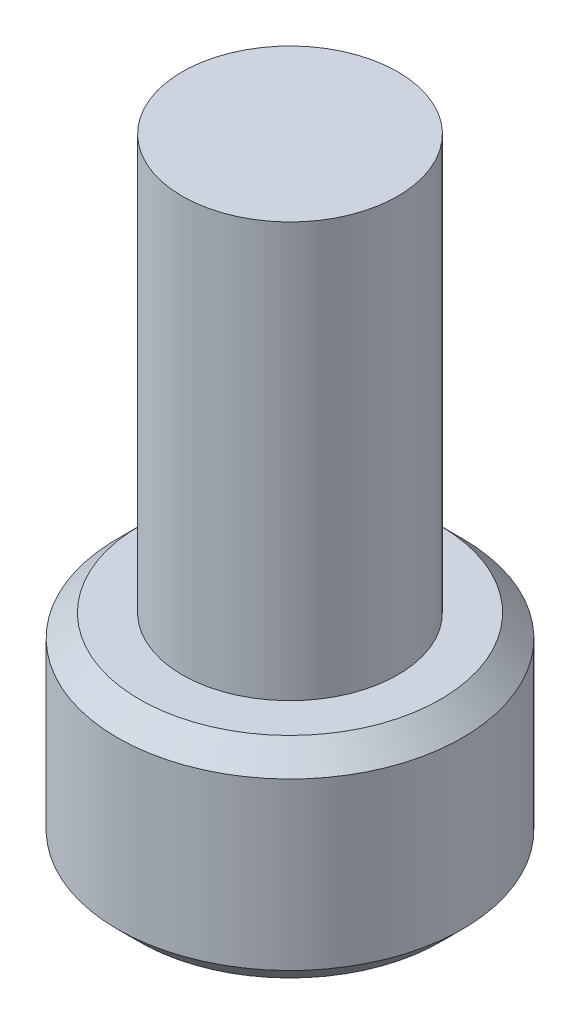
SolidWorks part; units mm, degrees
ref_plane "Front Plane" through (0, 0, 0) normal (0, 0, 1) x (1, 0, 0)
ref_plane "Top Plane" through (0, 0, 0) normal (0, 1, 0) x (1, 0, 0)
ref_plane "Right Plane" through (0, 0, 0) normal (1, 0, 0) x (0, 0, -1)
sketch "Sketch1" plane through (0, 0, 0) normal (0, 1, 0) x (1, 0, 0)
  circle A0 centre (0, 0) radius 2.4765
  dimension "D1" = 4.953
extrude "Boss-Extrude1" add sketch "Sketch1" along normal blind 9.525
sketch "Sketch2" plane through (0, 0, 0) normal (0, -1, 0) x (1, 0, 0)
  circle A0 centre (0, 0) radius 3.9624
  dimension "D1" = 7.9248
extrude "Boss-Extrude2" add sketch "Sketch2" along normal blind 4.826
sketch "Sketch3" plane through (0, -4.826, 0) normal (0, -1, 0) x (1, 0, 0)
  line L1 (2.2914, 0) -> (1.1457, 1.9844)
  line L2 (1.1457, 1.9844) -> (-1.1457, 1.9844)
  line L3 (-1.1457, 1.9844) -> (-2.2914, 0)
  line L4 (-2.2914, 0) -> (-1.1457, -1.9844)
  line L5 (-1.1457, -1.9844) -> (1.1457, -1.9844)
  line L6 (1.1457, -1.9844) -> (2.2914, 0)
  circle A0 centre (0, 0) radius 1.9844 construction
  dimension "D1" = 3.9688
extrude "Cut-Extrude1" cut sketch "Sketch3" against normal blind 2.286
chamfer "Chamfer1" distance 0.508 angle 45 2 edges at (0, -4.826, -3.9624) (0, 0, -3.9624)
